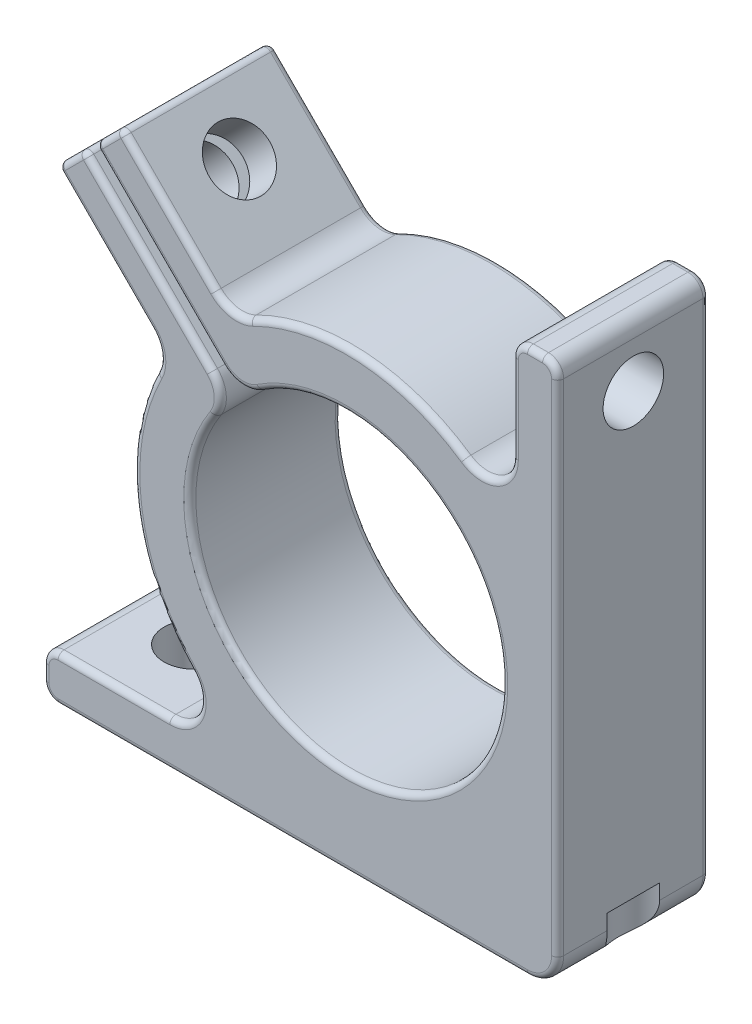
SolidWorks part; units mm, degrees
ref_plane "前视基准面" through (0, 0, 0) normal (0, 0, 1) x (1, 0, 0)
ref_plane "上视基准面" through (0, 0, 0) normal (0, 1, 0) x (1, 0, 0)
ref_plane "右视基准面" through (0, 0, 0) normal (1, 0, 0) x (0, 0, -1)
sketch "草图1" plane through (0, 0, 0) normal (0, 0, 1) x (1, 0, 0)
  line L0 (-9.5, -6.5) -> (-5.8095, -6.5)
  line L1 (-9.5, -8) -> (6, -8)
  line L2 (-10, -7) -> (-10, -7.5)
  line L3 (6, 10) -> (6.5, 10)
  line L4 (5.5, 9.5) -> (5.5, 6.6144)
  line L5 (0, 0) -> (-8.4853, 8.4853) construction
  line L6 (-7.2832, 9.4045) -> (-4.3129, 6.4342)
  line L7 (-8.8035, 8.1671) -> (-9.4045, 7.566)
  line L8 (0, 0) -> (0, -2.1091) construction
  line L9 (-8.1671, 8.5206) -> (-4.0812, 4.4347)
  line L10 (-8.1671, 8.8035) -> (-7.566, 9.4045)
  line L11 (-9.4045, 7.2832) -> (-6.4342, 4.3129)
  line L12 (7, 9.5) -> (7, -7)
  line L13 (-8.5206, 8.1671) -> (-4.4347, 4.0812)
  arc A0 (-4.3057, 2.8254) -> (-2.8254, 4.3057) centre (0, 0) ccw
  arc A1 (-6.2486, 3.1551) -> (-5.0833, -4.8125) centre (0, 0) ccw
  arc A2 (7, -7) -> (6, -8) centre (6, -7) cw
  arc A3 (-5.0833, -4.8125) -> (-5.8095, -6.5) centre (-5.8095, -5.5) cw
  arc A4 (5.5, 6.6144) -> (3.9375, 5.7876) centre (4.5, 6.6144) cw
  arc A5 (7, 9.5) -> (6.5, 10) centre (6.5, 9.5) ccw
  arc A6 (-9.5, -8) -> (-10, -7.5) centre (-9.5, -7.5) cw
  arc A7 (-10, -7) -> (-9.5, -6.5) centre (-9.5, -7) cw
  arc A8 (3.9375, 5.7876) -> (-3.1551, 6.2486) centre (0, 0) ccw
  arc A9 (-8.1671, 8.8035) -> (-8.1671, 8.5206) centre (-8.0257, 8.6621) ccw
  arc A10 (-7.2832, 9.4045) -> (-7.566, 9.4045) centre (-7.4246, 9.2631) ccw
  arc A11 (-4.3129, 6.4342) -> (-3.1551, 6.2486) centre (-3.6058, 7.1413) ccw
  arc A12 (-4.0812, 4.4347) -> (-2.8254, 4.3057) centre (-3.3741, 5.1418) ccw
  arc A13 (-9.4045, 7.2832) -> (-9.4045, 7.566) centre (-9.2631, 7.4246) cw
  arc A14 (-8.8035, 8.1671) -> (-8.5206, 8.1671) centre (-8.6621, 8.0257) cw
  arc A15 (-6.4342, 4.3129) -> (-6.2486, 3.1551) centre (-7.1413, 3.6058) cw
  arc A16 (-4.4347, 4.0812) -> (-4.3057, 2.8254) centre (-5.1418, 3.3741) cw
  arc A17 (6, 10) -> (5.5, 9.5) centre (6, 9.5) ccw
  point P13 (2.5981, -6.5)
  point P36 (-0.3, 12)
  dimension "D1" = 6.5
  dimension "D3" = 1
  dimension "D4" = 1.5
  dimension "D9" = 0.2
  dimension "D10" = 1
  dimension "D12" = 1
  dimension "D13" = 0.5
  dimension "D5" = 1.5
  dimension "D8" = 0.2
  dimension "D2" = 1.5
  dimension "D6" = 0.25
  dimension "D7" = 12
  dimension "D11" = 7
extrude "凸台-拉伸1" add sketch "草图1" along normal blind 5
sketch "草图3" plane through (0, -6.5, 0) normal (0, 1, 0) x (1, 0, 0)
  circle A0 centre (-7.5, -2.5) radius 1
  circle A1 centre (7.5, -2.5) radius 1
extrude "切除-拉伸1" cut sketch "草图3" against normal up to next
sketch "草图4" plane through (5.5, 0, 0) normal (-1, 0, 0) x (0, 0, 1)
  circle A0 centre (2.5, 8) radius 1
fillet "圆角2" radius 0.2 60 edges at (0.4541, 6.9853, 0) (-4.8909, -5.8953, 0) (-7.6547, -6.5, 0) (-9.8536, -6.6464, 0) (-10, -7.25, 0) (-9.8536, -7.8536, 0) (-1.75, -8, 0) (7, 1.25, 0) (-1.75, -8, 5) (-9.8536, -7.8536, 5) (-10, -7.25, 5) (-9.8536, -6.6464, 5) (-7.6547, -6.5, 5) (-4.8909, -5.8953, 5) (0.4541, 6.9853, 5) (7, 1.25, 5) (6.7071, -7.7071, 5) (6.7071, -7.7071, 0) (3.6416, -3.6416, 5) (4.9677, 5.7305, 5) (5.5, 8.0572, 5) (5.6464, 9.8536, 5) (6.25, 10, 5) (6.8536, 9.8536, 5) (3.6416, -3.6416, 0) (6.8536, 9.8536, 0) (6.25, 10, 0) (5.6464, 9.8536, 0) (5.5, 8.0572, 0) (4.9677, 5.7305, 0) (-6.9263, -1.0131, 5) (-6.1539, 3.764, 5) (-7.9194, 5.798, 5) (-9.4631, 7.4246, 5) (-9.104, 7.8666, 5) (-8.6621, 8.2257, 5) (-6.4777, 6.1241, 5) (-4.147, 3.4762, 5) (-3.4762, 4.147, 5) (-6.1241, 6.4777, 5) (-8.2257, 8.6621, 5) (-7.8666, 9.104, 5) (-7.4246, 9.4631, 5) (-5.798, 7.9194, 5) (-3.764, 6.1539, 5) (-3.764, 6.1539, 0) (-5.798, 7.9194, 0) (-7.4246, 9.4631, 0) (-7.8666, 9.104, 0) (-8.2257, 8.6621, 0) (-6.1241, 6.4777, 0) (-3.4762, 4.147, 0) (-4.147, 3.4762, 0) (-6.4777, 6.1241, 0) (-8.6621, 8.2257, 0) (-9.104, 7.8666, 0) (-9.4631, 7.4246, 0) (-7.9194, 5.798, 0) (-6.1539, 3.764, 0) (-6.9263, -1.0131, 0)
extrude "切除-拉伸2" cut sketch "草图4" against normal up to next
sketch "草图5" plane through (-1.0607, -1.0607, 0) normal (-0.7071, -0.7071, 0) x (0, 0, 1)
  circle A0 centre (2.5, 10) radius 1
extrude "切除-拉伸3" cut sketch "草图5" against normal blind 10
